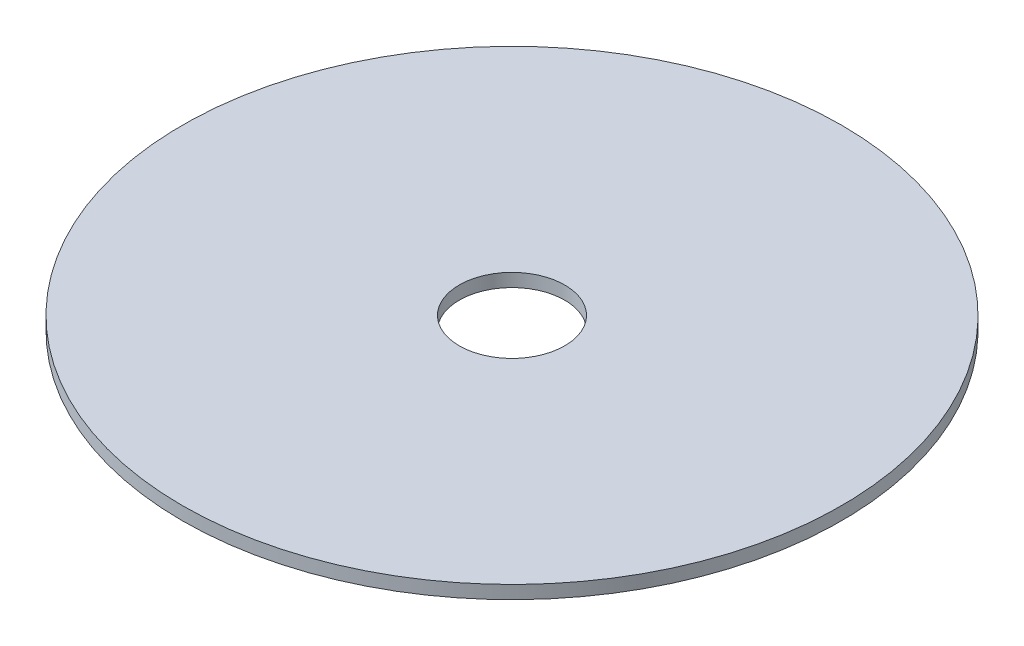
SolidWorks part; units mm, degrees
ref_plane "Front Plane" through (0, 0, 0) normal (0, 0, 1) x (1, 0, 0)
ref_plane "Top Plane" through (0, 0, 0) normal (0, 1, 0) x (1, 0, 0)
ref_plane "Right Plane" through (0, 0, 0) normal (1, 0, 0) x (0, 0, -1)
sketch "Sketch1" plane through (0, 0, 0) normal (0, 1, 0) x (1, 0, 0)
  circle A0 centre (0, 0) radius 37.5
  circle A1 centre (0, 0) radius 6
  dimension "D1" = 75
  dimension "D2" = 12
extrude "Boss-Extrude1" add sketch "Sketch1" along normal blind 1.5
